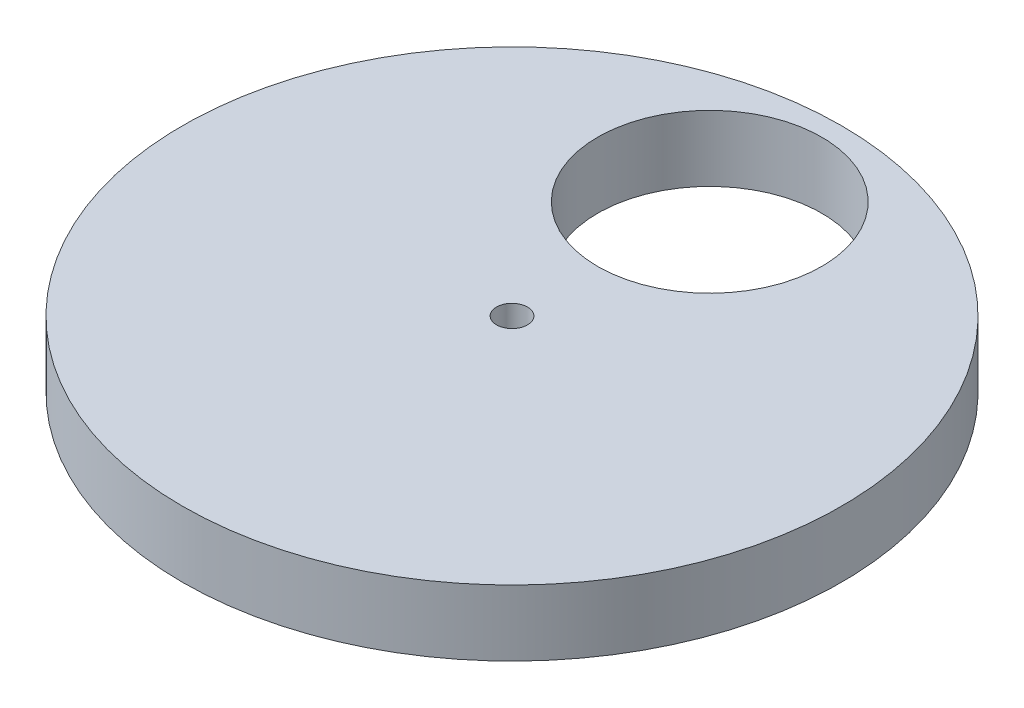
SolidWorks part; units mm, degrees
ref_plane "Front Plane" through (0, 0, 0) normal (0, 0, 1) x (1, 0, 0)
ref_plane "Top Plane" through (0, 0, 0) normal (0, 1, 0) x (1, 0, 0)
ref_plane "Right Plane" through (0, 0, 0) normal (1, 0, 0) x (0, 0, -1)
sketch "Sketch2" plane through (0, 0, 0) normal (0, 1, 0) x (1, 0, 0)
  circle A0 centre (0, 0) radius 50
  dimension "D1" = 100
extrude "Boss-Extrude2" add sketch "Sketch2" along normal blind 10
sketch "Sketch3" plane through (0, 10, 0) normal (0, 1, 0) x (1, 0, 0)
  line L0 (0, 0) -> (0, 30)
  line L1 (0, 0) -> (50, 0) construction
  circle A0 centre (0, 30) radius 17
  circle A3 centre (0, 0) radius 50 construction
  dimension "D1" = 30
  dimension "D2" = 34
extrude "Cut-Extrude1" cut sketch "Sketch3" against normal blind 118 contours A0
other "Cavity1"
other "Servo_SG90 - Updated<2>@ServoAssem1"
sketch "Sketch5" plane through (0, 10, 0) normal (0, 1, 0) x (1, 0, 0)
  circle A0 centre (0, 0) radius 2.35
  dimension "D1" = 4.7
extrude "Cut-Extrude2" cut sketch "Sketch5" against normal blind 6
